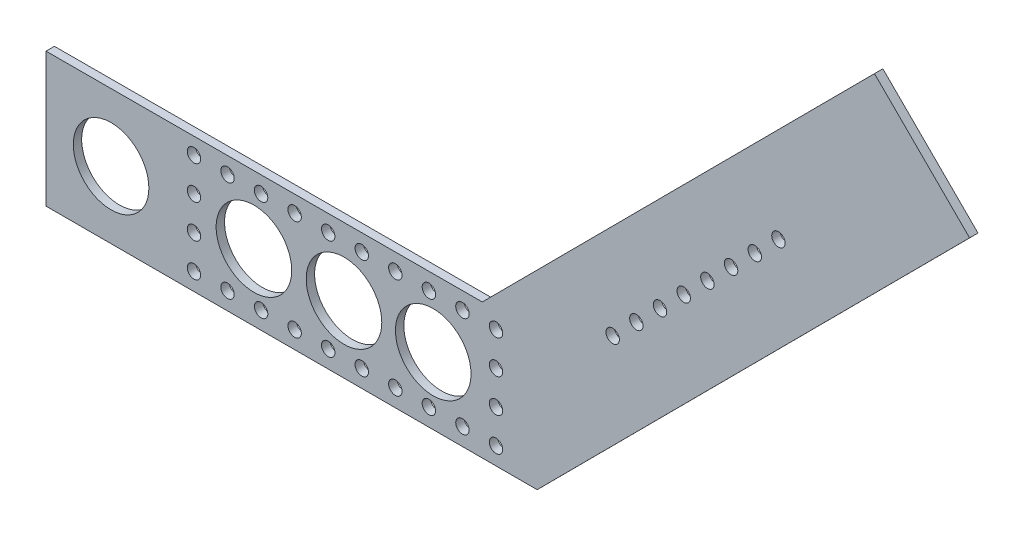
SolidWorks part; units mm, degrees
ref_plane "Front Plane" through (0, 0, 0) normal (0, 0, 1) x (1, 0, 0)
ref_plane "Top Plane" through (0, 0, 0) normal (0, 1, 0) x (1, 0, 0)
ref_plane "Right Plane" through (0, 0, 0) normal (1, 0, 0) x (0, 0, -1)
sketch "Sketch2" plane through (0, 0, 0) normal (0, 0, 1) x (1, 0, 0)
  line L0 (-77.4535, 2.5821) -> (-77.4535, -48.2179)
  line L1 (-77.4535, -48.2179) -> (108.4049, -48.2179)
  line L2 (108.4049, -48.2179) -> (272.0641, 116.1322)
  line L3 (272.0641, 116.1322) -> (236.0674, 151.9775)
  line L4 (236.0674, 151.9775) -> (87.6465, 2.9299)
  line L5 (87.6465, 2.9299) -> (-77.4535, 2.5821)
  circle A0 centre (-21.4612, -3.5013) radius 2.54 construction
  circle A1 centre (-21.4612, -16.2013) radius 2.54 construction
  circle A2 centre (-21.4612, -28.9013) radius 2.54 construction
  circle A3 centre (-21.4612, -41.6013) radius 2.54 construction
  circle A4 centre (-8.7612, -41.6013) radius 2.54 construction
  circle A5 centre (3.9388, -41.6013) radius 2.54 construction
  circle A6 centre (16.6388, -41.6013) radius 2.54 construction
  circle A7 centre (29.3388, -41.6013) radius 2.54 construction
  circle A8 centre (42.0388, -41.6013) radius 2.54 construction
  circle A9 centre (-8.7612, -3.5013) radius 2.54 construction
  circle A10 centre (3.9388, -3.5013) radius 2.54 construction
  circle A11 centre (16.6388, -3.5013) radius 2.54 construction
  circle A12 centre (29.3388, -3.5013) radius 2.54 construction
  circle A13 centre (42.0388, -3.5013) radius 2.54 construction
  circle A14 centre (54.7388, -3.5013) radius 2.54 construction
  circle A15 centre (67.4388, -3.5013) radius 2.54 construction
  circle A16 centre (80.1388, -3.5013) radius 2.54 construction
  circle A17 centre (92.8388, -3.5013) radius 2.54 construction
  circle A18 centre (92.8388, -16.2013) radius 2.54 construction
  circle A19 centre (92.8388, -28.9013) radius 2.54 construction
  circle A20 centre (54.7388, -41.6013) radius 2.54 construction
  circle A21 centre (67.4388, -41.6013) radius 2.54 construction
  circle A22 centre (80.1388, -41.6013) radius 2.54 construction
  circle A23 centre (92.8388, -41.6013) radius 2.54 construction
  circle A24 centre (69.0808, -22.8179) radius 14.3002 construction
  circle A25 centre (35.3107, -22.8179) radius 14.3002 construction
  circle A26 centre (1.237, -22.8179) radius 14.3002 construction
  circle A27 centre (-52.8273, -22.8179) radius 14.3002 construction
  circle A28 centre (-21.4612, -3.5013) radius 2.54
  circle A29 centre (-21.4612, -16.2013) radius 2.54
  circle A30 centre (-21.4612, -28.9013) radius 2.54
  circle A31 centre (-21.4612, -41.6013) radius 2.54
  circle A32 centre (-8.7612, -41.6013) radius 2.54
  circle A33 centre (3.9388, -41.6013) radius 2.54
  circle A34 centre (16.6388, -41.6013) radius 2.54
  circle A35 centre (29.3388, -41.6013) radius 2.54
  circle A36 centre (42.0388, -41.6013) radius 2.54
  circle A37 centre (-8.7612, -3.5013) radius 2.54
  circle A38 centre (3.9388, -3.5013) radius 2.54
  circle A39 centre (16.6388, -3.5013) radius 2.54
  circle A40 centre (29.3388, -3.5013) radius 2.54
  circle A41 centre (42.0388, -3.5013) radius 2.54
  circle A42 centre (54.7388, -3.5013) radius 2.54
  circle A43 centre (67.4388, -3.5013) radius 2.54
  circle A44 centre (80.1388, -3.5013) radius 2.54
  circle A45 centre (92.8388, -3.5013) radius 2.54
  circle A46 centre (92.8388, -16.2013) radius 2.54
  circle A47 centre (92.8388, -28.9013) radius 2.54
  circle A48 centre (54.7388, -41.6013) radius 2.54
  circle A49 centre (67.4388, -41.6013) radius 2.54
  circle A50 centre (80.1388, -41.6013) radius 2.54
  circle A51 centre (92.8388, -41.6013) radius 2.54
  circle A52 centre (69.0808, -22.8179) radius 14.3002
  circle A53 centre (35.3107, -22.8179) radius 14.3002
  circle A54 centre (1.237, -22.8179) radius 14.3002
  circle A55 centre (-52.8273, -22.8179) radius 14.3002
  circle A57 centre (136.9922, 16.487) radius 2.54
  circle A58 centre (145.9535, 25.4862) radius 2.54
  circle A59 centre (154.9148, 34.4853) radius 2.54
  circle A60 centre (163.8762, 43.4845) radius 2.54
  circle A61 centre (172.8375, 52.4836) radius 2.54
  circle A62 centre (181.7988, 61.4828) radius 2.54
  circle A63 centre (190.7601, 70.482) radius 2.54
  circle A64 centre (199.7214, 79.4811) radius 2.54
  dimension "D7" = 25.4
  dimension "D8" = 8
  dimension "D1" = 50.8
  dimension "D2" = 50.8
  dimension "D3" = 135
  dimension "D4" = 165.1
extrude "Boss-Extrude1" add sketch "Sketch2" along normal blind 3.175
